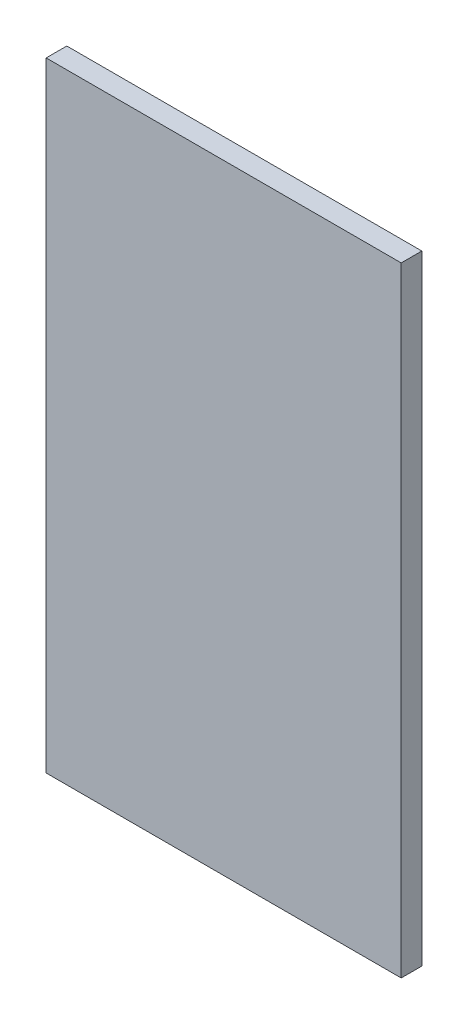
SolidWorks part; units mm, degrees
material "Бальса"
ref_plane "Спереди" through (0, 0, 0) normal (0, 0, 1) x (1, 0, 0)
ref_plane "Сверху" through (0, 0, 0) normal (0, 1, 0) x (1, 0, 0)
ref_plane "Справа" through (0, 0, 0) normal (1, 0, 0) x (0, 0, -1)
sketch "Эскиз2" plane through (0, 0, 0) normal (0, 0, 1) x (1, 0, 0)
  line L1 (0, 0) -> (172, 0)
  line L2 (0, 0) -> (0, 300)
  line L3 (0, 300) -> (172, 300)
  line L4 (172, 0) -> (172, 300)
  dimension "D1" = 172
  dimension "D2" = 300
extrude "Бобышка-Вытянуть1" add sketch "Эскиз2" along normal blind 10
sketch "Эскиз3" [suppressed] plane through (0, 0, 0) normal (-1, 0, 0) x (0, 0, 1)
  line L0 (10, 330) -> (0, 320)
  line L1 (0, 330) -> (0, 0) construction
  line L2 (0, 320) -> (0, 330)
  line L3 (0, 330) -> (10, 330)
  dimension "D1" = 45
sketch "Эскиз4" [suppressed] plane through (0, 0, 0) normal (-1, 0, 0) x (0, 0, 1)
  line L0 (0, 0) -> (10, 10)
  line L1 (10, 50) -> (10, 0) construction
  line L2 (10, 10) -> (10, 0)
  line L3 (10, 0) -> (0, 0)
  dimension "D1" = 45
sketch "Эскиз5" [suppressed] plane through (0, 0, 0) normal (0, -1, 0) x (-1, 0, 0)
  line L0 (-560, -10) -> (-550, 0)
  line L1 (0, 0) -> (-560, 0) construction
  line L2 (-550, 0) -> (-560, 0)
  line L3 (-560, 0) -> (-560, -10)
  dimension "D1" = 45
